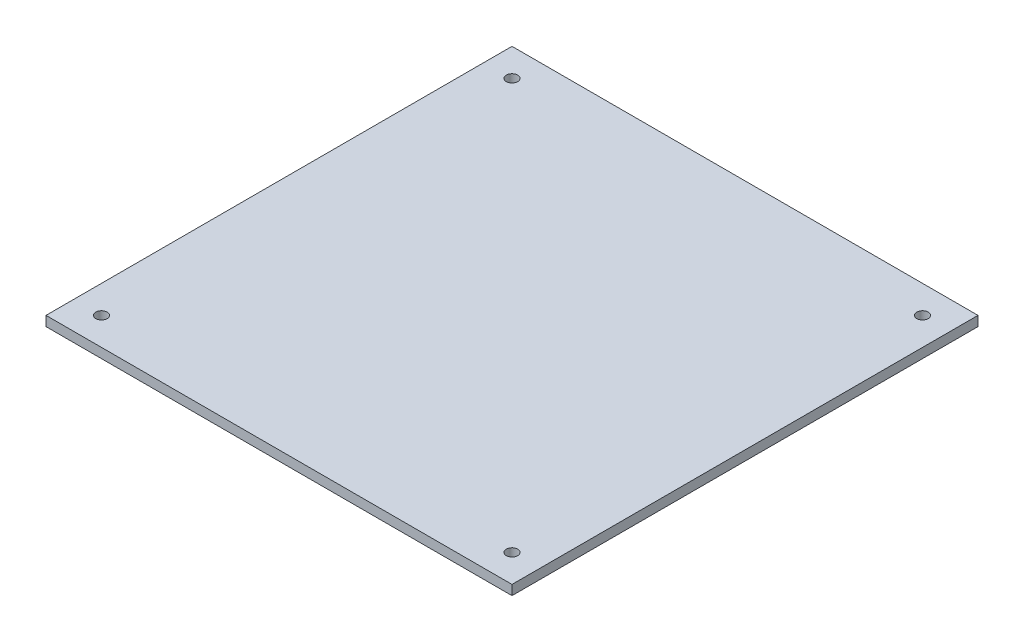
SolidWorks part; units mm, degrees
material "ABS PC"
ref_plane "Front Plane" through (0, 0, 0) normal (0, 0, 1) x (1, 0, 0)
ref_plane "Top Plane" through (0, 0, 0) normal (0, 1, 0) x (1, 0, 0)
ref_plane "Right Plane" through (0, 0, 0) normal (1, 0, 0) x (0, 0, -1)
sketch "Sketch1" plane through (0, 0, 0) normal (0, 1, 0) x (1, 0, 0)
  line L0 (133.35, 266.7) -> (133.35, 0) construction
  line L1 (0, 0) -> (266.7, 0)
  line L2 (0, 0) -> (0, 266.7)
  line L3 (0, 266.7) -> (266.7, 266.7)
  line L4 (266.7, 0) -> (266.7, 266.7)
  line L5 (0, 266.7) -> (31.75, 234.95) construction
  line L6 (31.75, 234.95) -> (234.95, 234.95) construction
  line L7 (31.75, 234.95) -> (31.75, 31.75) construction
  line L8 (31.75, 31.75) -> (234.95, 31.75) construction
  line L9 (234.95, 234.95) -> (234.95, 31.75) construction
  line L10 (31.75, 234.95) -> (234.95, 31.75) construction
  line L11 (31.75, 31.75) -> (234.95, 234.95) construction
  line L12 (234.95, 234.95) -> (266.7, 266.7) construction
  line L13 (31.75, 31.75) -> (0, 0) construction
  line L14 (234.95, 31.75) -> (266.7, 0) construction
  circle A0 centre (15.875, 250.825) radius 3.2639
  circle A1 centre (250.825, 250.825) radius 3.2639
  circle A2 centre (15.875, 15.875) radius 3.2639
  circle A3 centre (250.825, 15.875) radius 3.2639
  point P7 (133.35, 133.35)
  dimension "D3" = 6.5278
  dimension "D1" = 266.7
  dimension "D2" = 203.2
extrude "Boss-Extrude1" add sketch "Sketch1" along normal blind 5.588
fillet "Fillet1" [suppressed] radius 6.35
sketch "Sketch5" plane through (0, 5.588, 0) normal (0, 1, 0) x (1, 0, 0)
  line L0 (19.1389, 34.925) -> (19.1389, 24.8233)
  line L1 (12.6111, 34.925) -> (12.6111, 24.8233)
  line L2 (254.0889, 34.925) -> (254.0889, 24.8233)
  line L3 (247.5611, 34.925) -> (247.5611, 24.8233)
  line L4 (19.1389, 250.825) -> (19.1389, 240.7233)
  line L5 (12.6111, 250.825) -> (12.6111, 240.7233)
  line L6 (254.0889, 250.825) -> (254.0889, 240.7233)
  line L7 (247.5611, 250.825) -> (247.5611, 240.7233)
  arc A0 (12.6111, 24.8233) -> (19.1389, 24.8233) centre (15.875, 15.875) ccw
  arc A1 (19.1389, 34.925) -> (12.6111, 34.925) centre (15.875, 34.925) ccw
  circle A2 centre (15.875, 34.925) radius 9.525 construction
  arc A3 (254.0889, 34.925) -> (247.5611, 34.925) centre (250.825, 34.925) ccw
  arc A4 (247.5611, 24.8233) -> (254.0889, 24.8233) centre (250.825, 15.875) ccw
  circle A5 centre (250.825, 34.925) radius 9.525 construction
  arc A6 (12.6111, 240.7233) -> (19.1389, 240.7233) centre (15.875, 231.775) ccw
  circle A7 centre (15.875, 250.825) radius 9.525 construction
  arc A8 (19.1389, 250.825) -> (12.6111, 250.825) centre (15.875, 250.825) ccw
  arc A9 (247.5611, 240.7233) -> (254.0889, 240.7233) centre (250.825, 231.775) ccw
  circle A10 centre (250.825, 250.825) radius 9.525 construction
  arc A11 (254.0889, 250.825) -> (247.5611, 250.825) centre (250.825, 250.825) ccw
  dimension "D1" = 19.05
  dimension "D2" = 6.5278
  dimension "D3" = 19.05
extrude "Cut-Extrude2" [suppressed] cut sketch "Sketch5" against normal through all
sketch "Sketch6" plane through (0, 5.588, 0) normal (0, 1, 0) x (1, 0, 0)
  line L0 (266.7, 266.7) -> (0, 266.7) construction
  circle A0 centre (133.35, 266.7) radius 3.302
  dimension "D1" = 6.604
extrude "Cut-Extrude3" [suppressed] cut sketch "Sketch6" against normal through all
fillet "Fillet2" [suppressed] radius 1.5875
fillet "Fillet3" [suppressed] radius 0.762
